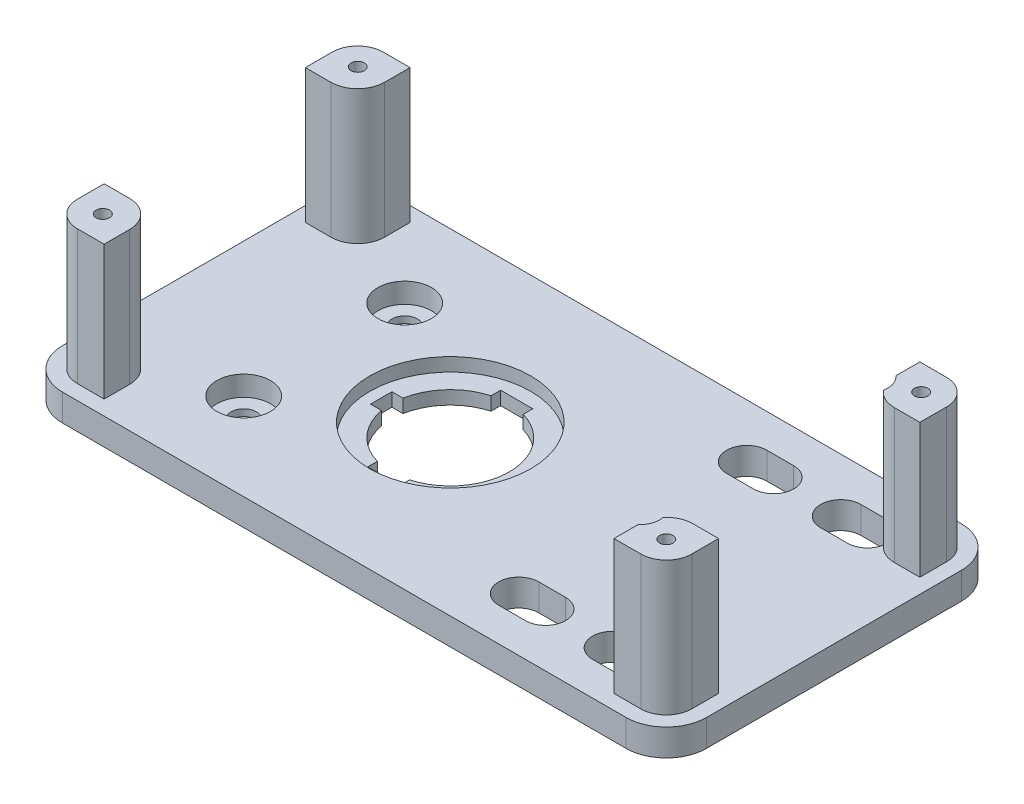
SolidWorks part; units mm, degrees
ref_plane "Front Plane" through (0, 0, 0) normal (0, 0, 1) x (1, 0, 0)
ref_plane "Top Plane" through (0, 0, 0) normal (0, 1, 0) x (1, 0, 0)
ref_plane "Right Plane" through (0, 0, 0) normal (1, 0, 0) x (0, 0, -1)
sketch "Sketch1" plane through (0, 0, 0) normal (0, 1, 0) x (1, 0, 0)
  line L1 (0, 0) -> (121.92, 0)
  line L2 (0, 0) -> (0, 63.5)
  line L3 (0, 63.5) -> (121.92, 63.5)
  line L4 (121.92, 0) -> (121.92, 63.5)
  dimension "D1" = 63.5
  dimension "D2" = 121.92
extrude "Boss-Extrude1" add sketch "Sketch1" along normal blind 5.08
fillet "Fillet1" radius 7.62 4 edges at (0, 2.54, 0) (0, 2.54, -63.5) (121.92, 2.54, -63.5) (121.92, 2.54, 0)
sketch "Sketch2" plane through (0, 5.08, 0) normal (0, 1, 0) x (1, 0, 0)
  line L0 (0, 55.88) -> (0, 7.62) construction
  line L1 (2.794, 60.706) -> (12.7, 60.706)
  line L2 (2.794, 60.706) -> (2.794, 50.8)
  line L3 (2.794, 50.8) -> (12.7, 50.8)
  line L4 (12.7, 60.706) -> (12.7, 50.8)
  line L5 (114.3, 63.5) -> (7.62, 63.5) construction
  line L6 (60.96, 63.5) -> (60.96, 0) construction
  line L7 (7.62, 0) -> (114.3, 0) construction
  line L8 (121.92, 31.75) -> (0, 31.75) construction
  line L9 (121.92, 7.62) -> (121.92, 55.88) construction
  line L10 (109.22, 60.706) -> (109.22, 50.8)
  line L11 (119.126, 50.8) -> (109.22, 50.8)
  line L12 (119.126, 60.706) -> (119.126, 50.8)
  line L13 (119.126, 60.706) -> (109.22, 60.706)
  line L14 (119.126, 2.794) -> (109.22, 2.794)
  line L15 (119.126, 2.794) -> (119.126, 12.7)
  line L16 (119.126, 12.7) -> (109.22, 12.7)
  line L17 (109.22, 2.794) -> (109.22, 12.7)
  line L18 (12.7, 2.794) -> (12.7, 12.7)
  line L19 (2.794, 12.7) -> (12.7, 12.7)
  line L20 (2.794, 2.794) -> (2.794, 12.7)
  line L21 (2.794, 2.794) -> (12.7, 2.794)
  dimension "D1" = 2.794
  dimension "D2" = 2.794
  dimension "D3" = 9.906
  dimension "D4" = 9.906
extrude "Boss-Extrude2" add sketch "Sketch2" along normal blind 22.86
sketch "Sketch5" plane through (0, 0, 0) normal (0, -1, 0) x (1, 0, 0)
  circle A0 centre (49.276, -31.75) radius 10.9982
  dimension "D1" = 24.13
  dimension "D2" = 21.9964
  dimension "D3" = 49.276
extrude "Cut-Extrude2" cut sketch "Sketch5" against normal up to next
sketch "Sketch6" plane through (0, 0, 0) normal (0, -1, 0) x (1, 0, 0)
  line L0 (0, -55.88) -> (0, -7.62) construction
  circle A0 centre (25.4, -16.51) radius 1.9939
  circle A1 centre (25.4, -46.99) radius 1.9939
  point P6 (0, -31.75)
  dimension "D1" = 3.9878
  dimension "D2" = 3.9878
  dimension "D3" = 25.4
  dimension "D4" = 15.24
  dimension "D5" = 15.24
extrude "Cut-Extrude3" cut sketch "Sketch6" against normal up to next
sketch "Sketch7" plane through (0, 5.08, 0) normal (0, 1, 0) x (1, 0, 0)
  circle A0 centre (25.4, 46.99) radius 5.08
  circle A1 centre (25.4, 16.51) radius 5.08
  dimension "D1" = 10.16
  dimension "D2" = 10.16
extrude "Cut-Extrude4" cut sketch "Sketch7" against normal blind 3.81
sketch "Sketch8" plane through (0, 5.08, 0) normal (0, 1, 0) x (1, 0, 0)
  circle A0 centre (49.276, 31.75) radius 15.24
  dimension "D1" = 30.48
extrude "Cut-Extrude5" cut sketch "Sketch8" against normal blind 2.54
sketch "Sketch9" plane through (0, 0, 0) normal (0, -1, 0) x (1, 0, 0)
  circle A0 centre (25.4, -16.51) radius 2.159
  circle A1 centre (25.4, -46.99) radius 2.159
  dimension "D1" = 4.318
  dimension "D2" = 4.318
extrude "Cut-Extrude6" cut sketch "Sketch9" against normal up to next
sketch "Sketch10" plane through (0, 0, 0) normal (0, -1, 0) x (1, 0, 0)
  line L0 (52.324, -42.5023) -> (52.324, -43.561)
  line L1 (46.228, -19.939) -> (52.324, -19.939)
  line L2 (46.228, -19.939) -> (46.228, -20.9977)
  line L3 (46.228, -43.561) -> (52.324, -43.561)
  line L4 (52.324, -19.939) -> (52.324, -20.9977)
  line L5 (36.957, -30.48) -> (38.1724, -30.48)
  line L6 (36.957, -30.48) -> (36.957, -33.02)
  line L7 (36.957, -33.02) -> (38.1724, -33.02)
  line L12 (46.228, -42.5023) -> (46.228, -43.561)
  arc A0 (38.1724, -33.02) -> (46.228, -42.5023) centre (49.276, -31.75) ccw
  arc A1 (46.228, -20.9977) -> (38.1724, -30.48) centre (49.276, -31.75) ccw
  arc A2 (52.324, -42.5023) -> (52.324, -20.9977) centre (49.276, -31.75) ccw
  dimension "D1" = 23.622
  dimension "D6" = 22.352
  dimension "D2" = 11.811
  dimension "D3" = 6.096
  dimension "D4" = 3.048
  dimension "D5" = 2.54
  dimension "D7" = 12.319
  dimension "D8" = 1.27
extrude "Cut-Extrude7" cut sketch "Sketch10" against normal up to next
sketch "Sketch11" plane through (0, 27.94, 0) normal (0, 1, 0) x (1, 0, 0)
  line L1 (131.5841, -12.1387) -> (-11.8062, -12.1387)
  line L2 (131.5841, -12.1387) -> (131.5841, 83.7008)
  line L3 (131.5841, 83.7008) -> (-11.8062, 83.7008)
  line L4 (-11.8062, -12.1387) -> (-11.8062, 83.7008)
extrude "Cut-Extrude8" cut sketch "Sketch11" against normal blind 5.08
sketch "Sketch14" plane through (0, 22.86, 0) normal (0, 1, 0) x (1, 0, 0)
  line L1 (119.126, 2.794) -> (109.22, 2.794)
  line L2 (119.126, 2.794) -> (119.126, 12.7)
  line L3 (119.126, 12.7) -> (109.22, 12.7)
  line L4 (109.22, 2.794) -> (109.22, 12.7)
  line L5 (12.7, 2.794) -> (2.794, 2.794)
  line L6 (12.7, 2.794) -> (12.7, 12.7)
  line L7 (12.7, 12.7) -> (2.794, 12.7)
  line L8 (2.794, 2.794) -> (2.794, 12.7)
  line L9 (119.126, 50.8) -> (109.22, 50.8)
  line L10 (119.126, 50.8) -> (119.126, 60.706)
  line L11 (119.126, 60.706) -> (109.22, 60.706)
  line L12 (109.22, 50.8) -> (109.22, 60.706)
  line L13 (12.7, 50.8) -> (2.794, 50.8)
  line L14 (12.7, 50.8) -> (12.7, 60.706)
  line L15 (12.7, 60.706) -> (2.794, 60.706)
  line L16 (2.794, 50.8) -> (2.794, 60.706)
extrude "Boss-Extrude4" add sketch "Sketch14" along normal blind 7.62
fillet "Fillet2" radius 4.826 4 edges at (2.794, 17.78, -2.794) (2.794, 17.78, -60.706) (119.126, 17.78, -2.794) (119.126, 17.78, -60.706)
fillet "Fillet3" radius 5.08 4 edges at (12.7, 17.78, -50.8) (12.7, 17.78, -12.7) (109.22, 17.78, -50.8) (109.22, 17.78, -12.7)
sketch "Sketch15" plane through (0, 30.48, 0) normal (0, 1, 0) x (1, 0, 0)
  circle A0 centre (114.3, 7.62) radius 1.27
  circle A1 centre (7.62, 7.62) radius 1.27
  circle A2 centre (114.3, 55.88) radius 1.27
  circle A3 centre (7.62, 55.88) radius 1.27
  dimension "D1" = 2.54
  dimension "D2" = 2.54
  dimension "D3" = 2.54
  dimension "D4" = 2.54
extrude "Cut-Extrude10" cut sketch "Sketch15" against normal blind 20.32
sketch "Sketch16" plane through (0, 0, 0) normal (0, -1, 0) x (1, 0, 0)
  circle A0 centre (25.4, -16.51) radius 2.413
  circle A1 centre (25.4, -46.99) radius 2.413
  dimension "D1" = 4.826
  dimension "D2" = 4.826
extrude "Cut-Extrude11" cut sketch "Sketch16" against normal up to next
sketch "Sketch17" plane through (0, 0, 0) normal (0, -1, 0) x (1, 0, 0)
  line L0 (36.957, -33.02) -> (38.1724, -33.02) construction
  line L1 (46.228, -19.177) -> (52.324, -19.177)
  line L2 (46.228, -19.177) -> (46.228, -44.323)
  line L3 (46.228, -44.323) -> (52.324, -44.323)
  line L4 (52.324, -19.177) -> (52.324, -44.323)
  line L5 (36.195, -29.718) -> (38.5764, -29.718)
  line L6 (36.195, -29.718) -> (36.195, -33.782)
  line L7 (36.195, -33.782) -> (38.5764, -33.782)
  line L8 (38.5764, -29.718) -> (38.5764, -33.782)
  dimension "D1" = 0.762
  dimension "D2" = 0.762
  dimension "D3" = 0.762
  dimension "D4" = 0.762
  dimension "D5" = 0.762
extrude "Cut-Extrude12" cut sketch "Sketch17" against normal up to next
sketch "Sketch18" plane through (0, 0, 0) normal (0, -1, 0) x (1, 0, 0)
  line L0 (106.68, -13.97) -> (101.6, -13.97)
  line L1 (88.9, -13.97) -> (83.82, -13.97)
  line L2 (106.68, -6.35) -> (101.6, -6.35)
  line L3 (88.9, -6.35) -> (83.82, -6.35)
  line L4 (121.92, -31.75) -> (0, -31.75) construction
  line L5 (121.92, -7.62) -> (121.92, -55.88) construction
  line L6 (0, -55.88) -> (0, -7.62) construction
  line L7 (88.9, -57.15) -> (83.82, -57.15)
  line L8 (106.68, -57.15) -> (101.6, -57.15)
  line L9 (88.9, -49.53) -> (83.82, -49.53)
  line L10 (106.68, -49.53) -> (101.6, -49.53)
  arc A0 (106.68, -13.97) -> (106.68, -6.35) centre (106.68, -10.16) ccw
  arc A1 (83.82, -6.35) -> (83.82, -13.97) centre (83.82, -10.16) ccw
  arc A2 (101.6, -6.35) -> (101.6, -13.97) centre (101.6, -10.16) ccw
  arc A3 (88.9, -13.97) -> (88.9, -6.35) centre (88.9, -10.16) ccw
  arc A4 (88.9, -49.53) -> (88.9, -57.15) centre (88.9, -53.34) cw
  arc A5 (101.6, -57.15) -> (101.6, -49.53) centre (101.6, -53.34) cw
  arc A6 (83.82, -57.15) -> (83.82, -49.53) centre (83.82, -53.34) cw
  arc A7 (106.68, -49.53) -> (106.68, -57.15) centre (106.68, -53.34) cw
  dimension "D1" = 7.62
  dimension "D3" = 7.62
  dimension "D4" = 7.62
  dimension "D6" = 7.62
  dimension "D8" = 7.62
  dimension "D2" = 30.48
  dimension "D5" = 10.16
  dimension "D7" = 5.08
  dimension "D9" = 5.08
extrude "Cut-Extrude13" cut sketch "Sketch18" against normal up to next
